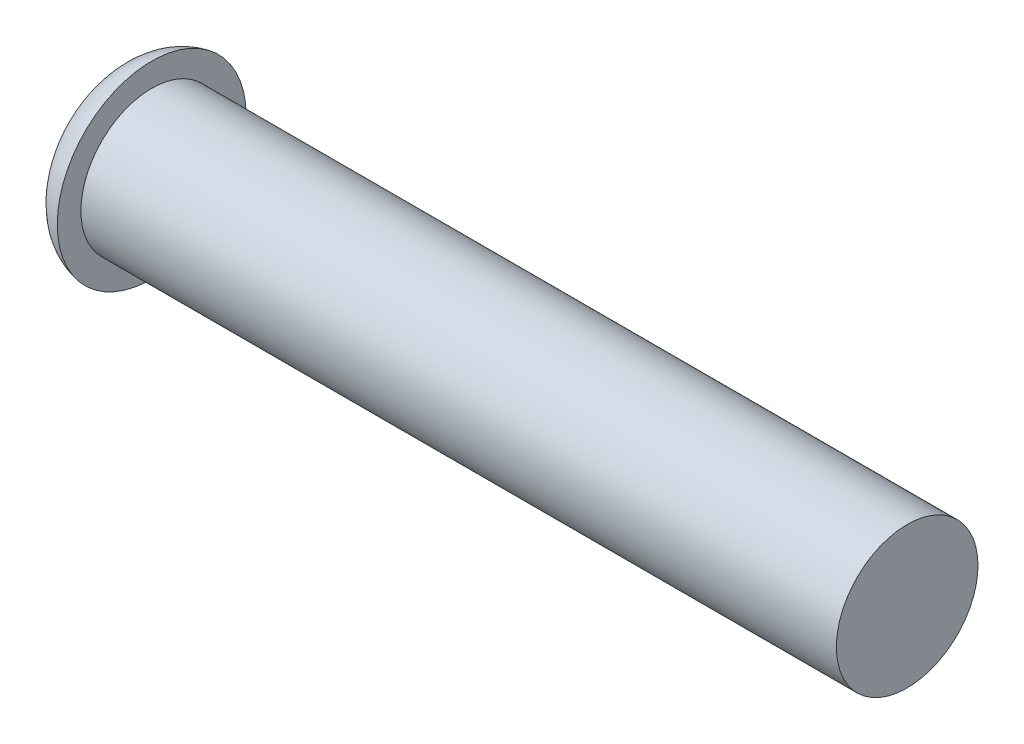
SolidWorks part; units mm, degrees
ref_plane "Front Plane" through (0, 0, 0) normal (0, 0, 1) x (1, 0, 0)
ref_plane "Top Plane" through (0, 0, 0) normal (0, 1, 0) x (1, 0, 0)
ref_plane "Right Plane" through (0, 0, 0) normal (1, 0, 0) x (0, 0, -1)
sketch "Sketch1" plane through (0, 0, 0) normal (0, 1, 0) x (1, 0, 0)
  line L0 (-16.95, 1.5) -> (-16.95, 0.906)
  line L1 (0, 0) -> (-16, 0)
  line L2 (0, 0) -> (0, 1.5)
  line L3 (0, 1.5) -> (-16.95, 1.5)
  line L5 (-16, 0) -> (-16, -0.5)
  spline S0 degree 3 poles (-16, -0.5) (-16.5908, -0.3906) (-16.8879, 0.1976) (-16.95, 0.906) knots 0 0 0 0 0.787143 0.787143 0.787143 0.787143
  dimension "D2" = 1.5
  dimension "D3" = 0.5
  dimension "D6" = 16
revolve "Revolve1" add sketch "Sketch1" angle 360 about L3
sketch "Sketch3" plane through (-16.95, 0, 0) normal (-1, 0, 0) x (0, 0, 1)
  line L1 (-0.9248, 1.0012) -> (-2.0795, 0.9988)
  line L2 (-2.0795, 0.9988) -> (-2.6547, -0.0025)
  line L3 (-2.6547, -0.0025) -> (-2.0752, -1.0012)
  line L4 (-2.0752, -1.0012) -> (-0.9205, -0.9988)
  line L5 (-0.9205, -0.9988) -> (-0.3453, 0.0025)
  line L6 (-0.3453, 0.0025) -> (-0.9248, 1.0012)
  circle A0 centre (-1.5, 0) radius 1 construction
  circle A1 centre (-1.5, 0) radius 0.594
  circle A2 centre (-1.5, 0) radius 0.594
  dimension "D2" = 2
  dimension "D1" = 0
extrude "Cut-Extrude1" cut sketch "Sketch3" against normal blind 1.5
sketch "Sketch4" plane through (-16.95, 0, 0) normal (-1, 0, 0) x (0, 0, 1)
  circle A1 centre (-1.5, 0) radius 0.594
  circle A2 centre (-1.5, 0) radius 0.594
  dimension "D1" = 0
extrude "Cut-Extrude2" cut sketch "Sketch4" against normal blind 1.5
